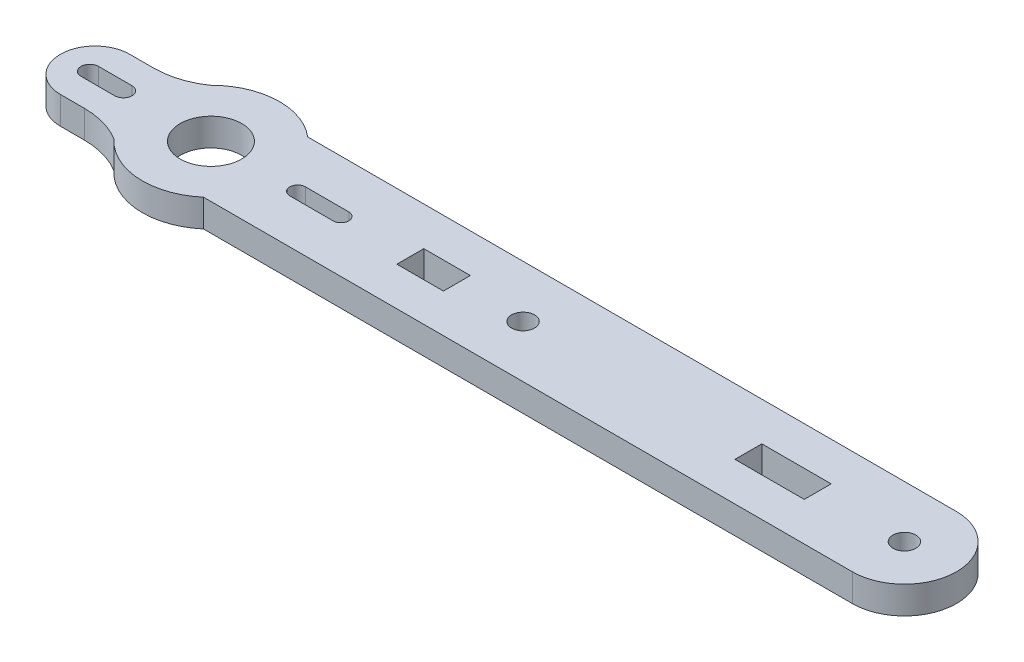
SolidWorks part; units mm, degrees
ref_plane "Front Plane" through (0, 0, 0) normal (0, 0, 1) x (1, 0, 0)
ref_plane "Top Plane" through (0, 0, 0) normal (0, 1, 0) x (1, 0, 0)
ref_plane "Right Plane" through (0, 0, 0) normal (1, 0, 0) x (0, 0, -1)
sketch "Sketch1" plane through (0, 0, 0) normal (0, 1, 0) x (1, 0, 0)
  line L0 (-41.381, -4.957) -> (-41.2088, 5.9181) construction
  line L1 (-30.4202, 6.3945) -> (44.3022, 6.39)
  line L3 (-30.4203, -5.6151) -> (44.3022, -5.6151)
  line L7 (-46.1509, 4.39) -> (-48.9097, 4.39)
  line L8 (-48.9097, -3.6104) -> (-46.1509, -3.6104)
  line L12 (34.32, 1.8852) -> (34.32, 1.9351)
  line L13 (34.32, 1.9351) -> (26.3341, 1.9351)
  line L14 (26.3341, 1.9351) -> (26.3341, 1.8852)
  line L15 (26.3341, 1.8852) -> (26.3341, -1.1149)
  line L16 (26.3341, -1.1149) -> (26.3341, -1.165)
  line L17 (26.3341, -1.165) -> (34.32, -1.165)
  line L18 (34.32, -1.165) -> (34.32, -1.1149)
  line L19 (34.32, -1.1149) -> (34.32, 1.8852)
  line L20 (-7.2331, 1.9349) -> (-12.5968, 1.9349)
  line L21 (-12.5968, 1.9349) -> (-12.5968, -1.1648)
  line L22 (-12.5968, -1.1648) -> (-7.2331, -1.1648)
  line L23 (-7.2331, -1.1648) -> (-7.2331, 1.9349)
  line L24 (-20.5827, -0.5149) -> (-25.5738, -0.5149)
  line L25 (-25.5738, 1.2851) -> (-20.5827, 1.2851)
  line L43 (-49.5122, 1.3852) -> (-45.6381, 1.3852)
  line L44 (-45.6381, -0.6149) -> (-49.5122, -0.6149)
  arc A0 (44.3022, -5.6151) -> (44.3022, 6.39) centre (44.3022, 0.3875) ccw
  circle A1 centre (44.3022, 0.3875) radius 1.3226
  circle A2 centre (0.3831, 0.3852) radius 1.3226
  arc A3 (-25.5738, 1.2851) -> (-25.5738, -0.5149) centre (-25.5738, 0.3851) ccw
  arc A4 (-20.5827, 1.2851) -> (-20.5827, -0.5149) centre (-20.5827, 0.3851) cw
  circle A5 centre (-35.5599, 0.3898) radius 3.5436
  arc A6 (-30.4202, 6.3945) -> (-41.2088, 5.9181) centre (-35.5599, 0.3898) ccw
  arc A7 (-49.5122, 1.3852) -> (-49.5122, -0.6149) centre (-49.5122, 0.3852) ccw
  arc A8 (-45.6381, 1.3852) -> (-45.6381, -0.6149) centre (-45.6381, 0.3852) cw
  arc A9 (-48.9097, 4.39) -> (-48.9097, -3.6104) centre (-48.9097, 0.3898) ccw
  arc A10 (-46.1509, -3.6104) -> (-41.381, -4.957) centre (-46.1509, -12.7317) cw
  arc A11 (-46.1509, 4.39) -> (-41.2088, 5.9181) centre (-46.1509, 13.1455) ccw
  arc A12 (-41.381, -4.957) -> (-30.4203, -5.6151) centre (-35.5599, 0.3898) ccw
  point P22 (0.3831, 0.3852)
  point P27 (-35.5599, 0.3898)
  dimension "D1" = 2.6452
extrude "Boss-Extrude1" add sketch "Sketch1" along normal blind 3.175
